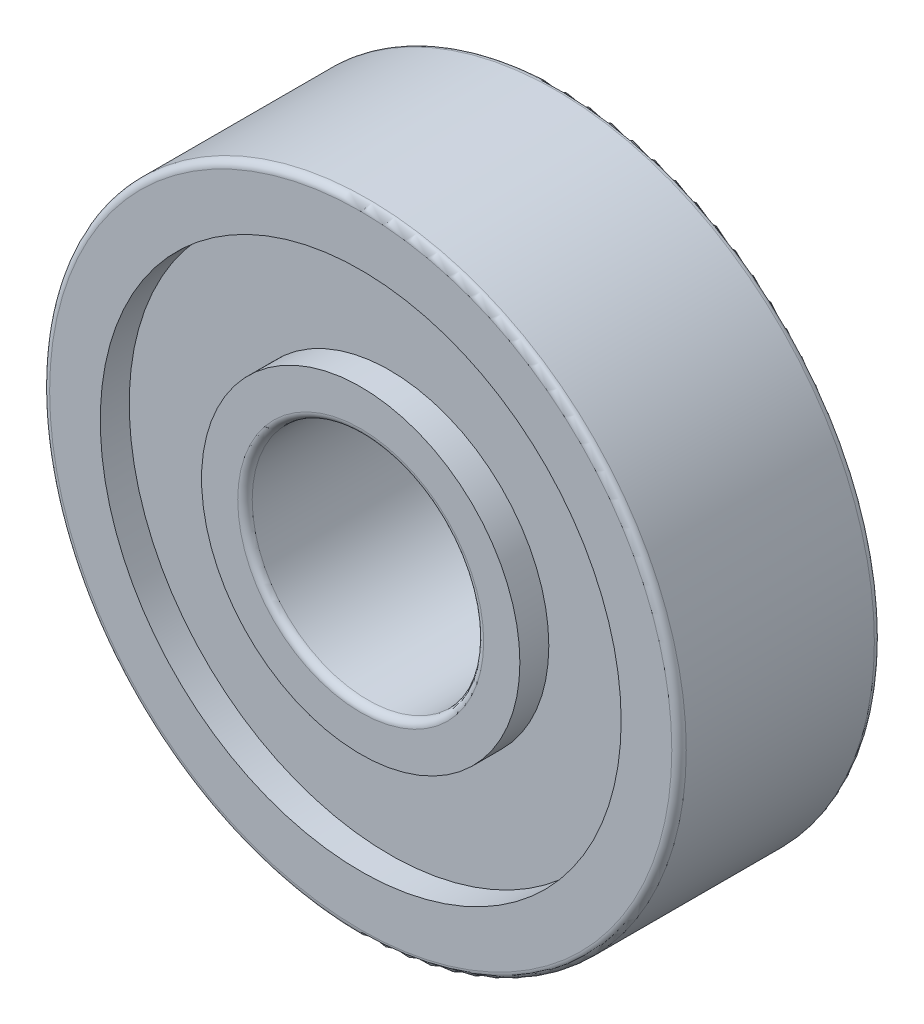
SolidWorks part; units mm, degrees
material "Acier allié"
ref_plane "Plan de face" through (0, 0, 0) normal (0, 0, 1) x (1, 0, 0)
ref_plane "Plan de dessus" through (0, 0, 0) normal (0, 1, 0) x (1, 0, 0)
ref_plane "Plan de droite" through (0, 0, 0) normal (1, 0, 0) x (0, 0, -1)
sketch "Esquisse1" plane through (0, 0, 0) normal (0, 0, 1) x (1, 0, 0)
  circle A0 centre (0, 0) radius 11
  circle A1 centre (0, 0) radius 4
  dimension "D1" = 22
  dimension "D2" = 8
extrude "Extrusion1" add sketch "Esquisse1" along normal blind 7
fillet "Congé1" radius 0.25 4 edges at (4, 0, 0) (4, 0, 7) (11, 0, 0) (11, 0, 7)
sketch "Esquisse2" plane through (0, 0, 7) normal (0, 0, 1) x (1, 0, 0)
  circle A0 centre (0, 0) radius 5.5
  circle A1 centre (0, 0) radius 9
  dimension "D1" = 11
  dimension "D2" = 18
extrude "Extrusion2" cut sketch "Esquisse2" against normal blind 1
sketch "Esquisse3" plane through (0, 0, 0) normal (0, 0, -1) x (-1, 0, 0)
  circle A0 centre (0, 0) radius 5.5
  circle A1 centre (0, 0) radius 9
  dimension "D1" = 11
  dimension "D2" = 18
extrude "Extrusion3" cut sketch "Esquisse3" against normal blind 1
